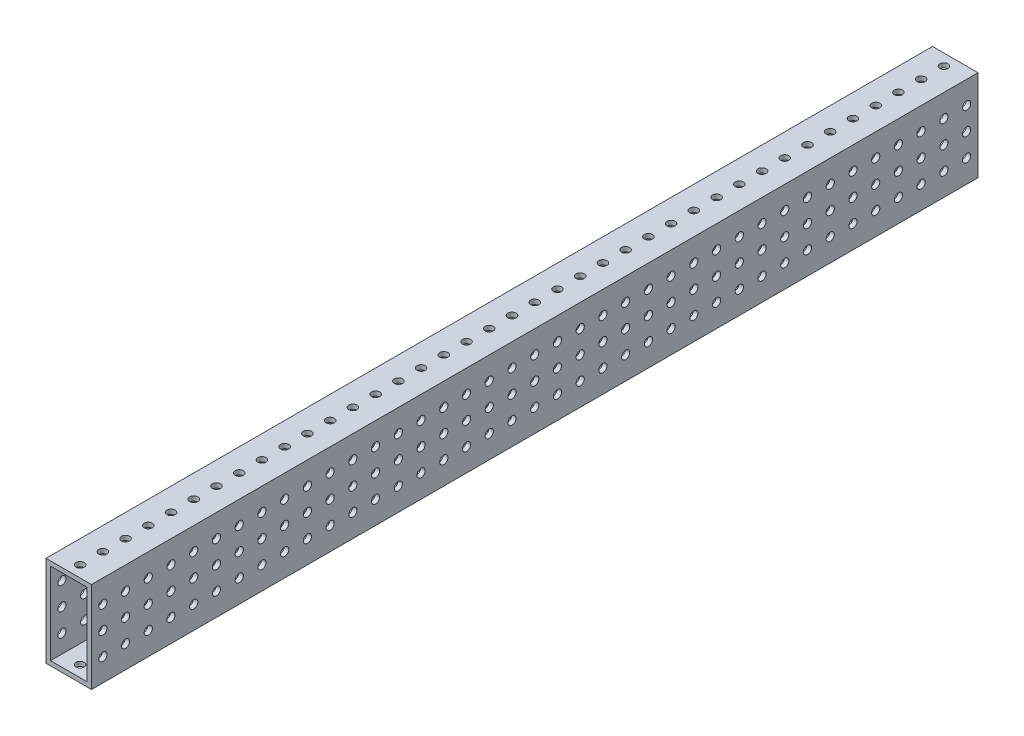
SolidWorks part; units mm, degrees
ref_plane "Front Plane" through (0, 0, 0) normal (0, 0, 1) x (1, 0, 0)
ref_plane "Top Plane" through (0, 0, 0) normal (0, 1, 0) x (1, 0, 0)
ref_plane "Right Plane" through (0, 0, 0) normal (1, 0, 0) x (0, 0, -1)
sketch "Sketch1" plane through (0, 0, 0) normal (0, 0, 1) x (1, 0, 0)
  line L1 (-24.6845, 23.3131) -> (0.7155, 23.3131)
  line L2 (-24.6845, 23.3131) -> (-24.6845, -27.4869)
  line L3 (-24.6845, -27.4869) -> (0.7155, -27.4869)
  line L4 (0.7155, 23.3131) -> (0.7155, -27.4869)
  line L5 (-24.6845, 23.3131) -> (0.7155, -27.4869) construction
  line L6 (-24.6845, -27.4869) -> (0.7155, 23.3131) construction
  line L7 (-22.1445, -24.9469) -> (-1.8245, -24.9469)
  line L8 (-22.1445, -24.9469) -> (-22.1445, 20.7731)
  line L9 (-22.1445, 20.7731) -> (-1.8245, 20.7731)
  line L10 (-1.8245, -24.9469) -> (-1.8245, 20.7731)
  line L11 (-22.1445, -24.9469) -> (-1.8245, 20.7731) construction
  line L12 (-22.1445, 20.7731) -> (-1.8245, -24.9469) construction
  point P0 (-11.9845, -2.0869)
  point P5 (-11.9845, -2.0869)
  dimension "D1" = 50.8
  dimension "D2" = 25.4
  dimension "D3" = 20.32
  dimension "D4" = 45.72
extrude "Boss-Extrude1" add sketch "Sketch1" along normal blind 495.3
sketch "Sketch2" plane through (0.7155, 0, 0) normal (1, 0, 0) x (0, 0, -1)
  line L0 (-495.3, 23.3131) -> (0, 23.3131) construction
  line L1 (-495.3, -27.4869) -> (-495.3, 23.3131) construction
  circle A0 centre (-488.95, 10.6131) radius 2.286
  circle A1 centre (-476.25, 10.6131) radius 2.286
  circle A2 centre (-463.55, 10.6131) radius 2.286
  circle A3 centre (-450.85, 10.6131) radius 2.286
  circle A4 centre (-438.15, 10.6131) radius 2.286
  circle A5 centre (-425.45, 10.6131) radius 2.286
  circle A6 centre (-412.75, 10.6131) radius 2.286
  circle A7 centre (-400.05, 10.6131) radius 2.286
  circle A8 centre (-387.35, 10.6131) radius 2.286
  circle A9 centre (-374.65, 10.6131) radius 2.286
  circle A10 centre (-361.95, 10.6131) radius 2.286
  circle A11 centre (-349.25, 10.6131) radius 2.286
  circle A12 centre (-336.55, 10.6131) radius 2.286
  circle A13 centre (-323.85, 10.6131) radius 2.286
  circle A14 centre (-311.15, 10.6131) radius 2.286
  circle A15 centre (-298.45, 10.6131) radius 2.286
  circle A16 centre (-285.75, 10.6131) radius 2.286
  circle A17 centre (-273.05, 10.6131) radius 2.286
  circle A18 centre (-260.35, 10.6131) radius 2.286
  circle A19 centre (-247.65, 10.6131) radius 2.286
  circle A20 centre (-234.95, 10.6131) radius 2.286
  circle A21 centre (-222.25, 10.6131) radius 2.286
  circle A22 centre (-209.55, 10.6131) radius 2.286
  circle A23 centre (-196.85, 10.6131) radius 2.286
  circle A24 centre (-184.15, 10.6131) radius 2.286
  circle A25 centre (-171.45, 10.6131) radius 2.286
  circle A26 centre (-158.75, 10.6131) radius 2.286
  circle A27 centre (-146.05, 10.6131) radius 2.286
  circle A28 centre (-133.35, 10.6131) radius 2.286
  circle A29 centre (-120.65, 10.6131) radius 2.286
  circle A30 centre (-107.95, 10.6131) radius 2.286
  circle A31 centre (-95.25, 10.6131) radius 2.286
  circle A32 centre (-82.55, 10.6131) radius 2.286
  circle A33 centre (-69.85, 10.6131) radius 2.286
  circle A34 centre (-57.15, 10.6131) radius 2.286
  circle A35 centre (-44.45, 10.6131) radius 2.286
  circle A36 centre (-31.75, 10.6131) radius 2.286
  circle A37 centre (-19.05, 10.6131) radius 2.286
  circle A38 centre (-6.35, 10.6131) radius 2.286
  circle A39 centre (-476.25, -2.0869) radius 2.286
  circle A40 centre (-463.55, -2.0869) radius 2.286
  circle A41 centre (-450.85, -2.0869) radius 2.286
  circle A42 centre (-438.15, -2.0869) radius 2.286
  circle A43 centre (-425.45, -2.0869) radius 2.286
  circle A44 centre (-412.75, -2.0869) radius 2.286
  circle A45 centre (-400.05, -2.0869) radius 2.286
  circle A46 centre (-387.35, -2.0869) radius 2.286
  circle A47 centre (-374.65, -2.0869) radius 2.286
  circle A48 centre (-361.95, -2.0869) radius 2.286
  circle A49 centre (-349.25, -2.0869) radius 2.286
  circle A50 centre (-336.55, -2.0869) radius 2.286
  circle A51 centre (-323.85, -2.0869) radius 2.286
  circle A52 centre (-311.15, -2.0869) radius 2.286
  circle A53 centre (-298.45, -2.0869) radius 2.286
  circle A54 centre (-285.75, -2.0869) radius 2.286
  circle A55 centre (-273.05, -2.0869) radius 2.286
  circle A56 centre (-260.35, -2.0869) radius 2.286
  circle A57 centre (-247.65, -2.0869) radius 2.286
  circle A58 centre (-234.95, -2.0869) radius 2.286
  circle A59 centre (-222.25, -2.0869) radius 2.286
  circle A60 centre (-209.55, -2.0869) radius 2.286
  circle A61 centre (-196.85, -2.0869) radius 2.286
  circle A62 centre (-184.15, -2.0869) radius 2.286
  circle A63 centre (-171.45, -2.0869) radius 2.286
  circle A64 centre (-158.75, -2.0869) radius 2.286
  circle A65 centre (-146.05, -2.0869) radius 2.286
  circle A66 centre (-133.35, -2.0869) radius 2.286
  circle A67 centre (-120.65, -2.0869) radius 2.286
  circle A68 centre (-107.95, -2.0869) radius 2.286
  circle A69 centre (-95.25, -2.0869) radius 2.286
  circle A70 centre (-82.55, -2.0869) radius 2.286
  circle A71 centre (-69.85, -2.0869) radius 2.286
  circle A72 centre (-57.15, -2.0869) radius 2.286
  circle A73 centre (-44.45, -2.0869) radius 2.286
  circle A74 centre (-31.75, -2.0869) radius 2.286
  circle A75 centre (-19.05, -2.0869) radius 2.286
  circle A76 centre (-6.35, -2.0869) radius 2.286
  circle A77 centre (-476.25, -14.7869) radius 2.286
  circle A78 centre (-463.55, -14.7869) radius 2.286
  circle A79 centre (-450.85, -14.7869) radius 2.286
  circle A80 centre (-438.15, -14.7869) radius 2.286
  circle A81 centre (-425.45, -14.7869) radius 2.286
  circle A82 centre (-412.75, -14.7869) radius 2.286
  circle A83 centre (-400.05, -14.7869) radius 2.286
  circle A84 centre (-387.35, -14.7869) radius 2.286
  circle A85 centre (-374.65, -14.7869) radius 2.286
  circle A86 centre (-361.95, -14.7869) radius 2.286
  circle A87 centre (-349.25, -14.7869) radius 2.286
  circle A88 centre (-336.55, -14.7869) radius 2.286
  circle A89 centre (-323.85, -14.7869) radius 2.286
  circle A90 centre (-311.15, -14.7869) radius 2.286
  circle A91 centre (-298.45, -14.7869) radius 2.286
  circle A92 centre (-285.75, -14.7869) radius 2.286
  circle A93 centre (-273.05, -14.7869) radius 2.286
  circle A94 centre (-260.35, -14.7869) radius 2.286
  circle A95 centre (-247.65, -14.7869) radius 2.286
  circle A96 centre (-234.95, -14.7869) radius 2.286
  circle A97 centre (-222.25, -14.7869) radius 2.286
  circle A98 centre (-209.55, -14.7869) radius 2.286
  circle A99 centre (-196.85, -14.7869) radius 2.286
  circle A100 centre (-184.15, -14.7869) radius 2.286
  circle A101 centre (-171.45, -14.7869) radius 2.286
  circle A102 centre (-158.75, -14.7869) radius 2.286
  circle A103 centre (-146.05, -14.7869) radius 2.286
  circle A104 centre (-133.35, -14.7869) radius 2.286
  circle A105 centre (-120.65, -14.7869) radius 2.286
  circle A106 centre (-107.95, -14.7869) radius 2.286
  circle A107 centre (-95.25, -14.7869) radius 2.286
  circle A108 centre (-82.55, -14.7869) radius 2.286
  circle A109 centre (-69.85, -14.7869) radius 2.286
  circle A110 centre (-57.15, -14.7869) radius 2.286
  circle A111 centre (-44.45, -14.7869) radius 2.286
  circle A112 centre (-31.75, -14.7869) radius 2.286
  circle A113 centre (-19.05, -14.7869) radius 2.286
  circle A114 centre (-6.35, -14.7869) radius 2.286
  circle A115 centre (-488.95, -2.0869) radius 2.286
  circle A116 centre (-488.95, -14.7869) radius 2.286
  dimension "D1" = 4.572
  dimension "D2" = 12.7
  dimension "D3" = 6.35
  dimension "D4" = 39
  dimension "D5" = 3
extrude "Cut-Extrude1" cut sketch "Sketch2" against normal blind 25.4
sketch "Sketch4" plane through (0, 23.3131, 0) normal (0, 1, 0) x (1, 0, 0)
  line L0 (-24.6845, -495.3) -> (-24.6845, 0) construction
  line L1 (0.7155, 0) -> (-24.6845, 0) construction
  circle A0 centre (-11.9845, -6.35) radius 2.286
  circle A1 centre (-11.9845, -19.05) radius 2.286
  circle A2 centre (-11.9845, -31.75) radius 2.286
  circle A3 centre (-11.9845, -44.45) radius 2.286
  circle A4 centre (-11.9845, -57.15) radius 2.286
  circle A5 centre (-11.9845, -69.85) radius 2.286
  circle A6 centre (-11.9845, -82.55) radius 2.286
  circle A7 centre (-11.9845, -95.25) radius 2.286
  circle A8 centre (-11.9845, -107.95) radius 2.286
  circle A9 centre (-11.9845, -120.65) radius 2.286
  circle A10 centre (-11.9845, -133.35) radius 2.286
  circle A11 centre (-11.9845, -146.05) radius 2.286
  circle A12 centre (-11.9845, -158.75) radius 2.286
  circle A13 centre (-11.9845, -171.45) radius 2.286
  circle A14 centre (-11.9845, -184.15) radius 2.286
  circle A15 centre (-11.9845, -196.85) radius 2.286
  circle A16 centre (-11.9845, -209.55) radius 2.286
  circle A17 centre (-11.9845, -222.25) radius 2.286
  circle A18 centre (-11.9845, -234.95) radius 2.286
  circle A19 centre (-11.9845, -247.65) radius 2.286
  circle A20 centre (-11.9845, -260.35) radius 2.286
  circle A21 centre (-11.9845, -273.05) radius 2.286
  circle A22 centre (-11.9845, -285.75) radius 2.286
  circle A23 centre (-11.9845, -298.45) radius 2.286
  circle A24 centre (-11.9845, -311.15) radius 2.286
  circle A25 centre (-11.9845, -323.85) radius 2.286
  circle A26 centre (-11.9845, -336.55) radius 2.286
  circle A27 centre (-11.9845, -349.25) radius 2.286
  circle A28 centre (-11.9845, -361.95) radius 2.286
  circle A29 centre (-11.9845, -374.65) radius 2.286
  circle A30 centre (-11.9845, -387.35) radius 2.286
  circle A31 centre (-11.9845, -400.05) radius 2.286
  circle A32 centre (-11.9845, -412.75) radius 2.286
  circle A33 centre (-11.9845, -425.45) radius 2.286
  circle A34 centre (-11.9845, -438.15) radius 2.286
  circle A35 centre (-11.9845, -450.85) radius 2.286
  circle A36 centre (-11.9845, -463.55) radius 2.286
  circle A37 centre (-11.9845, -476.25) radius 2.286
  circle A38 centre (-11.9845, -488.95) radius 2.286
  dimension "D1" = 12.7
  dimension "D3" = 4.572
  dimension "D4" = 39
  dimension "D2" = 6.35
extrude "Cut-Extrude2" cut sketch "Sketch4" against normal blind 50.8
